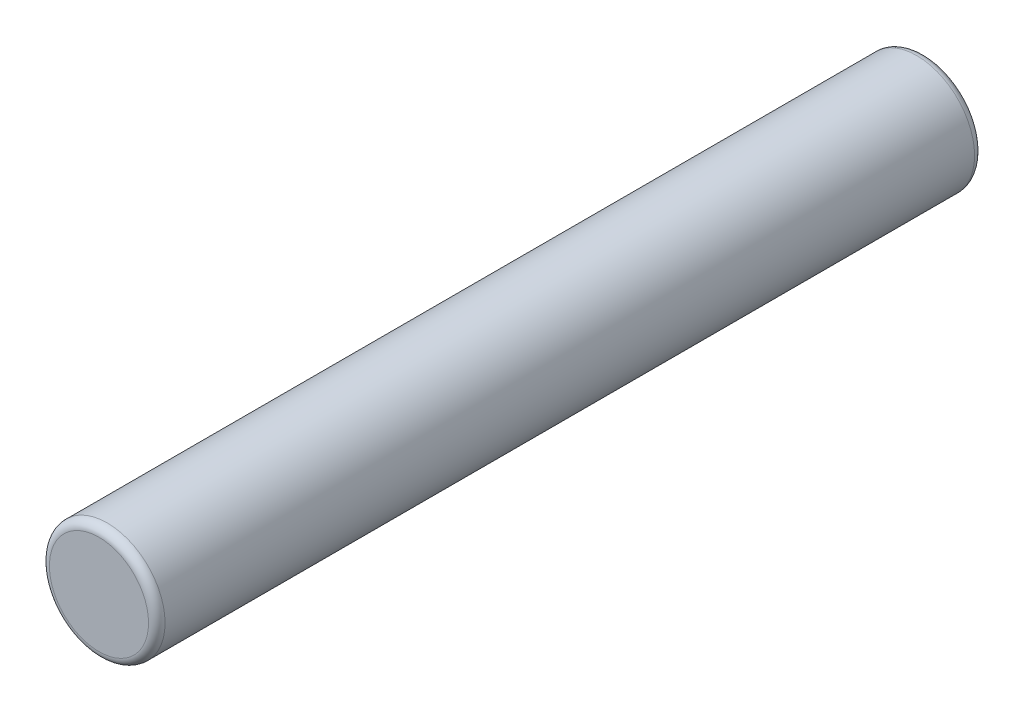
SolidWorks part; units mm, degrees
material "A-1"
ref_plane "Front Plane" through (0, 0, 0) normal (0, 0, 1) x (1, 0, 0)
ref_plane "Top Plane" through (0, 0, 0) normal (0, 1, 0) x (1, 0, 0)
ref_plane "Right Plane" through (0, 0, 0) normal (1, 0, 0) x (0, 0, -1)
sketch "Sketch2" plane through (0, 0, 0) normal (0, 0, 1) x (1, 0, 0)
  circle A0 centre (0, 0) radius 5.5562
  dimension "D1" = 11.1125
extrude "Boss-Extrude1" add sketch "Sketch2" along normal mid plane 79.375
fillet "Fillet1" radius 0.7937 2 edges at (5.5562, 0, 39.6875) (5.5562, 0, -39.6875)
